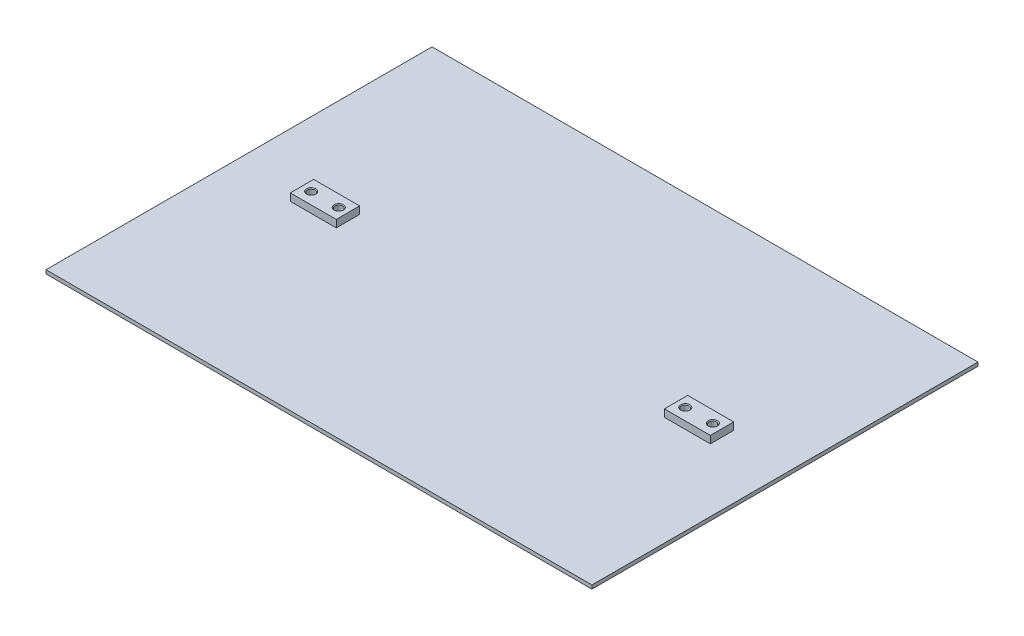
SolidWorks part; units mm, degrees
ref_plane "Front Plane" through (0, 0, 0) normal (0, 0, 1) x (1, 0, 0)
ref_plane "Top Plane" through (0, 0, 0) normal (0, 1, 0) x (1, 0, 0)
ref_plane "Right Plane" through (0, 0, 0) normal (1, 0, 0) x (0, 0, -1)
sketch "Sketch1" plane through (0, 0, 0) normal (0, 1, 0) x (1, 0, 0)
  line L1 (-148.5, -105) -> (148.5, -105)
  line L2 (-148.5, -105) -> (-148.5, 105)
  line L3 (-148.5, 105) -> (148.5, 105)
  line L4 (148.5, -105) -> (148.5, 105)
  line L5 (-148.5, -105) -> (148.5, 105) construction
  line L6 (-148.5, 105) -> (148.5, -105) construction
  point P0 (0, 0)
  dimension "D1" = 297
  dimension "D2" = 210
extrude "Boss-Extrude1" add sketch "Sketch1" along normal blind 2 contours L3 L4 L1 L2
sketch "Sketch4" plane through (0, 2, 0) normal (0, 1, 0) x (1, 0, 0)
  line L0 (0, 0) -> (148.5, 0) construction
  line L1 (148.5, -105) -> (148.5, 105) construction
  line L2 (0, -1.1) -> (0, 1.1) construction
  line L3 (34.25, -6.35) -> (114.25, -6.35) construction
  line L4 (34.25, -6.35) -> (34.25, 6.35) construction
  line L5 (34.25, 6.35) -> (114.25, 6.35) construction
  line L6 (114.25, -6.35) -> (114.25, 6.35) construction
  line L7 (34.25, -6.35) -> (114.25, 6.35) construction
  line L8 (34.25, 6.35) -> (114.25, -6.35) construction
  line L9 (89.25, -6.35) -> (114.25, -6.35)
  line L10 (89.25, -6.35) -> (89.25, 6.35)
  line L11 (89.25, 6.35) -> (114.25, 6.35)
  line L12 (114.25, -6.35) -> (114.25, 6.35)
  line L13 (89.25, -6.35) -> (114.25, 6.35) construction
  line L14 (89.25, 6.35) -> (114.25, -6.35) construction
  line L15 (-89.25, -6.35) -> (-114.25, -6.35)
  line L16 (-114.25, -6.35) -> (-114.25, 6.35)
  line L17 (-89.25, 6.35) -> (-114.25, 6.35)
  line L18 (-89.25, -6.35) -> (-89.25, 6.35)
  point P5 (74.25, 0)
  point P10 (101.75, 0)
  point P19 (109.25, 0)
  point P20 (94.25, 0)
  dimension "D1" = 12.7
  dimension "D2" = 80
  dimension "D3" = 5
  dimension "D4" = 5
  dimension "D5" = 20
extrude "Boss-Extrude2" add sketch "Sketch4" along normal blind 4
sketch "Sketch2" plane through (0, 6, 0) normal (0, 1, 0) x (1, 0, 0)
  line L2 (0, -1.1) -> (0, 1.1) construction
  line L4 (34.25, 6.35) -> (114.25, 6.35) construction
  line L5 (34.25, 6.35) -> (34.25, -6.35) construction
  line L6 (34.25, -6.35) -> (114.25, -6.35) construction
  line L7 (114.25, 6.35) -> (114.25, -6.35) construction
  line L8 (34.25, 6.35) -> (114.25, -6.35) construction
  line L9 (34.25, -6.35) -> (114.25, 6.35) construction
  line L10 (0, 0) -> (148.5, 0) construction
  line L11 (148.5, -105) -> (148.5, 105) construction
  line L13 (0, 0) -> (-148.5, 0) construction
  line L14 (-148.5, -105) -> (-148.5, 105) construction
  line L15 (-34.25, -6.35) -> (-114.25, 6.35) construction
  line L16 (-34.25, 6.35) -> (-114.25, -6.35) construction
  line L17 (-114.25, 6.35) -> (-114.25, -6.35) construction
  line L18 (-34.25, -6.35) -> (-114.25, -6.35) construction
  line L19 (-34.25, 6.35) -> (-34.25, -6.35) construction
  line L20 (-34.25, 6.35) -> (-114.25, 6.35) construction
  point P5 (109.25, 0)
  point P6 (94.25, 0)
  point P10 (0, 0)
  point P13 (74.25, 0)
  point P140 (74.25, 0)
  point P148 (-74.25, 0)
  point P149 (-94.25, 0)
  point P150 (-109.25, 0)
  dimension "D1" = 5
  dimension "D2" = 20
  dimension "D3" = 80
  dimension "D4" = 12.7
hole_wizard "M5 Tapped Hole1" positions "Sketch2" profile "Sketch3" tap size "M5" standard "ISO"
sketch "Sketch3" plane through (-109.25, 6, 0) normal (1, 0, 0) x (0, 0, 1)
  line L0 (0, 0) -> (0, 6)
  line L1 (0, 6) -> (2.1, 6)
  line L2 (2.1, 6) -> (2.1, 0.425)
  line L3 (2.1, 0.425) -> (2.525, 0)
  line L5 (2.525, 0) -> (0, 0)
  line L6 (-2.1, 0.425) -> (-2.525, 0) construction
  line L11 (0, -6.35) -> (0, 107.95) construction
  dimension "Thru Tap Drill Dia." = 4.2
  dimension "Thru Tap Drill Depth" = 6
  dimension "Near C'Sink Dia." = 5.05
  dimension "Near C'Sink Angle" = 90
cosmetic thread "Hole Thread1" parameters "D2"=5
cosmetic thread "Hole Thread2" parameters "D2"=5
cosmetic thread "Hole Thread3" parameters "D2"=5
cosmetic thread "Hole Thread4" parameters "D2"=5
equation "\"l\"= 297"
equation "\"w\"= 210mm"
equation "\"D1@Sketch1\"=\"l\""
equation "\"D2@Sketch1\"=\"w\""
